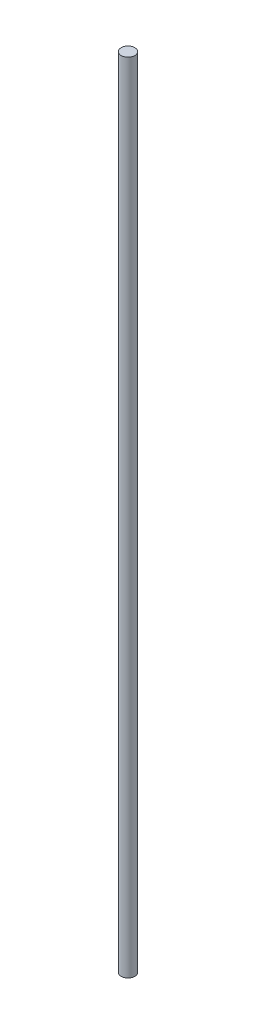
SolidWorks part; units mm, degrees
ref_plane "前视基准面" through (0, 0, 0) normal (0, 0, 1) x (1, 0, 0)
ref_plane "上视基准面" through (0, 0, 0) normal (0, 1, 0) x (1, 0, 0)
ref_plane "右视基准面" through (0, 0, 0) normal (1, 0, 0) x (0, 0, -1)
sketch "草图1" plane through (0, 0, 0) normal (0, 1, 0) x (1, 0, 0)
  circle A0 centre (0, 0) radius 6
  dimension "D1" = 12
extrude "凸台-拉伸1" add sketch "草图1" along normal blind 700
